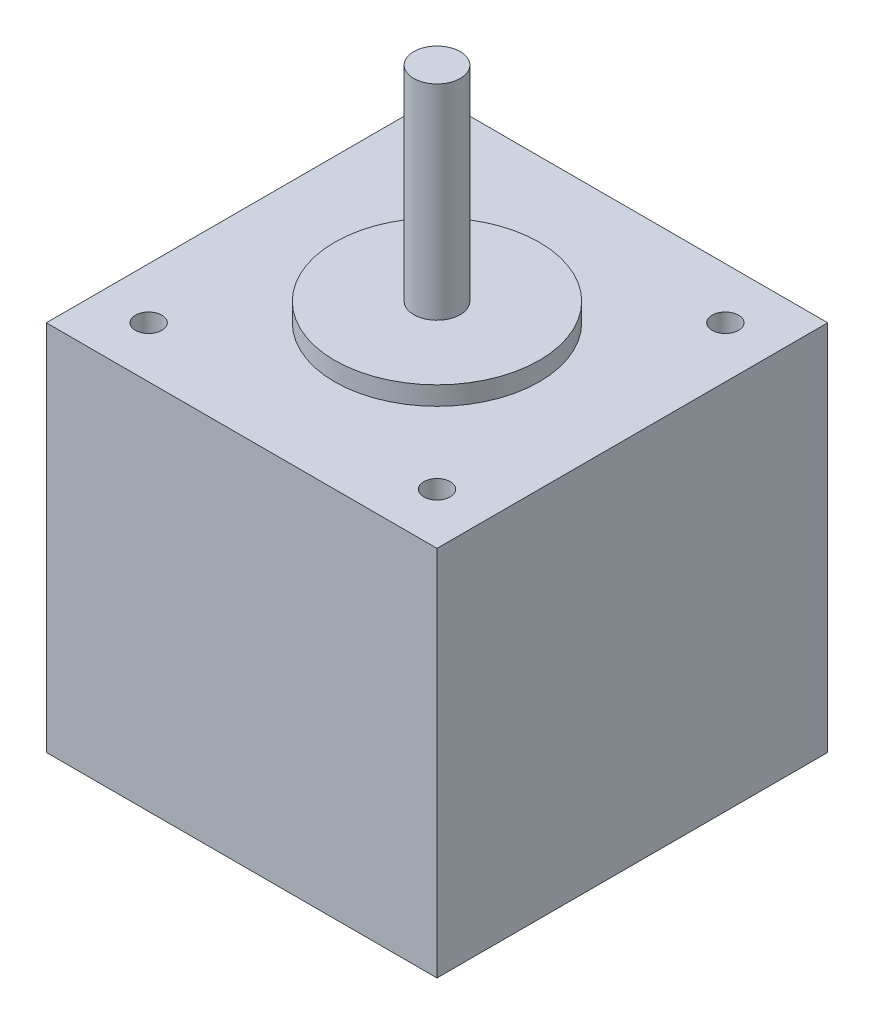
SolidWorks part; units mm, degrees
ref_plane "Front Plane" through (0, 0, 0) normal (0, 0, 1) x (1, 0, 0)
ref_plane "Top Plane" through (0, 0, 0) normal (0, 1, 0) x (1, 0, 0)
ref_plane "Right Plane" through (0, 0, 0) normal (1, 0, 0) x (0, 0, -1)
sketch "Sketch1" plane through (0, 0, 0) normal (0, 1, 0) x (1, 0, 0)
  line L1 (-21, -21) -> (21, -21)
  line L2 (-21, -21) -> (-21, 21)
  line L3 (-21, 21) -> (21, 21)
  line L4 (21, -21) -> (21, 21)
  line L5 (-21, -21) -> (21, 21) construction
  line L6 (-21, 21) -> (21, -21) construction
  point P0 (0, 0)
  dimension "D1" = 42
  dimension "D2" = 42
extrude "Boss-Extrude1" add sketch "Sketch1" along normal blind 40
sketch "Sketch2" plane through (0, 40, 0) normal (0, 1, 0) x (1, 0, 0)
  circle A0 centre (0, 0) radius 11
  dimension "D1" = 22
extrude "Boss-Extrude2" add sketch "Sketch2" along normal blind 2
sketch "Sketch3" plane through (0, 42, 0) normal (0, 1, 0) x (1, 0, 0)
  circle A0 centre (0, 0) radius 2.5
  dimension "D1" = 5
extrude "Boss-Extrude3" add sketch "Sketch3" along normal blind 22
sketch "Sketch4" plane through (0, 40, 0) normal (0, 1, 0) x (1, 0, 0)
  circle A0 centre (-15.5, 15.5) radius 1.42
  circle A1 centre (15.5, 15.5) radius 1.42
  circle A2 centre (15.5, -15.5) radius 1.42
  circle A3 centre (-15.5, -15.5) radius 1.42
  dimension "D1" = 2.84
  dimension "D2" = 15.5
  dimension "D3" = 15.5
  dimension "D4" = 2
  dimension "D5" = 2
extrude "Cut-Extrude1" cut sketch "Sketch4" against normal blind 5
